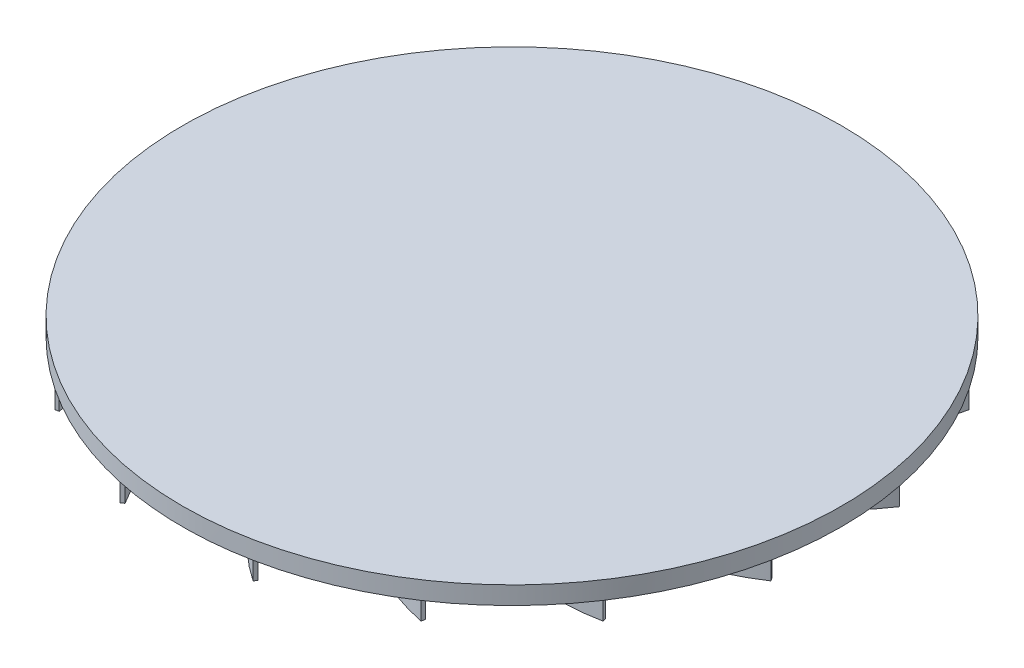
SolidWorks part; units mm, degrees
ref_plane "Front Plane" through (0, 0, 0) normal (0, 0, 1) x (1, 0, 0)
ref_plane "Top Plane" through (0, 0, 0) normal (0, 1, 0) x (1, 0, 0)
ref_plane "Right Plane" through (0, 0, 0) normal (1, 0, 0) x (0, 0, -1)
sketch "Sketch1" plane through (0, 0, 0) normal (0, 1, 0) x (1, 0, 0)
  circle A0 centre (0, 0) radius 233.68
extrude "Boss-Extrude1" add sketch "Sketch1" along normal blind 12.7
sketch "Sketch7" plane through (0, 0, 0) normal (0, -1, 0) x (-1, 0, 0)
  arc A1 (-10.5647, -7.0591) -> (-194.2978, -129.8257) centre (-163.8145, 23.4242) cw
  circle A2 centre (0, 0) radius 233.68 construction
  arc A3 (10.5647, 7.0591) -> (194.2978, 129.8257) centre (163.8145, -23.4242) cw
  arc A4 (-12.4619, -2.4788) -> (-229.1899, -45.5887) centre (-142.3808, 84.3303) cw
  arc A5 (-12.4619, 2.4788) -> (-229.1899, 45.5887) centre (-99.2709, 132.3978) cw
  arc A6 (12.4619, -2.4788) -> (229.1899, -45.5887) centre (99.2709, -132.3978) cw
  arc A7 (12.4619, 2.4788) -> (229.1899, 45.5887) centre (142.3808, -84.3303) cw
  arc A8 (-7.0591, -10.5647) -> (-129.8257, -194.2978) centre (-160.3089, -41.048) cw
  arc A9 (7.0591, 10.5647) -> (129.8257, 194.2978) centre (160.3089, 41.048) cw
  arc A10 (-2.4788, 12.4619) -> (-45.5887, 229.1899) centre (84.3303, 142.3808) cw
  arc A11 (2.6959, -12.4167) -> (49.5817, -228.3594) centre (-81.8325, -143.8309) cw
  arc A12 (7.0591, -10.5647) -> (129.8257, -194.2978) centre (-23.4242, -163.8145) cw
  arc A13 (-2.4788, -12.4619) -> (-45.5887, -229.1899) centre (-132.3978, -99.2709) cw
  arc A14 (2.6959, 12.4167) -> (45.8062, 229.1465) centre (132.616, 99.2265) cw
  arc A15 (10.5647, -7.0591) -> (194.2978, -129.8257) centre (41.048, -160.3089) cw
  arc A16 (-7.0591, 10.5647) -> (-129.8257, 194.2978) centre (23.4242, 163.8145) cw
  arc A17 (-10.5647, 7.0591) -> (-194.2978, 129.8257) centre (-41.048, 160.3089) cw
extrude "Extrude-Thin12" add sketch "Sketch7" along normal blind 12.7 thin
